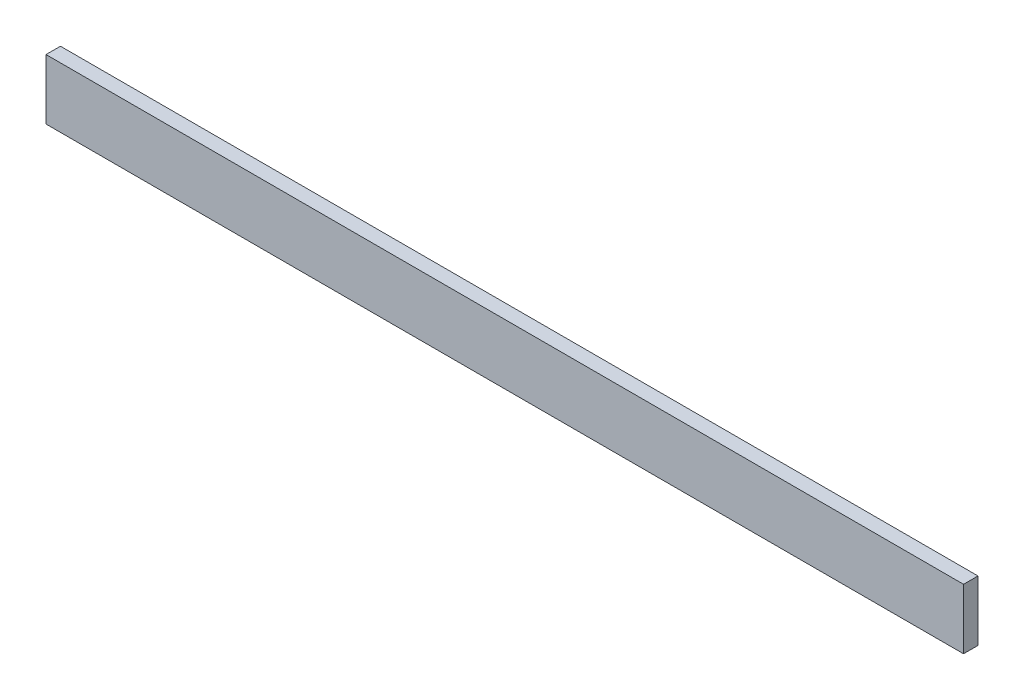
SolidWorks part; units mm, degrees
ref_plane "Front Plane" through (0, 0, 0) normal (0, 0, 1) x (1, 0, 0)
ref_plane "Top Plane" through (0, 0, 0) normal (0, 1, 0) x (1, 0, 0)
ref_plane "Right Plane" through (0, 0, 0) normal (1, 0, 0) x (0, 0, -1)
sketch "Sketch1" plane through (0, 0, 0) normal (0, 0, 1) x (1, 0, 0)
  line L1 (76.2, -5) -> (-76.2, -5)
  line L2 (76.2, -5) -> (76.2, 5)
  line L3 (76.2, 5) -> (-76.2, 5)
  line L4 (-76.2, -5) -> (-76.2, 5)
  line L5 (76.2, -5) -> (-76.2, 5) construction
  line L6 (76.2, 5) -> (-76.2, -5) construction
  point P0 (0, 0)
  dimension "D1" = 152.4
  dimension "D2" = 10
extrude "Boss-Extrude1" add sketch "Sketch1" along normal blind 2.4
